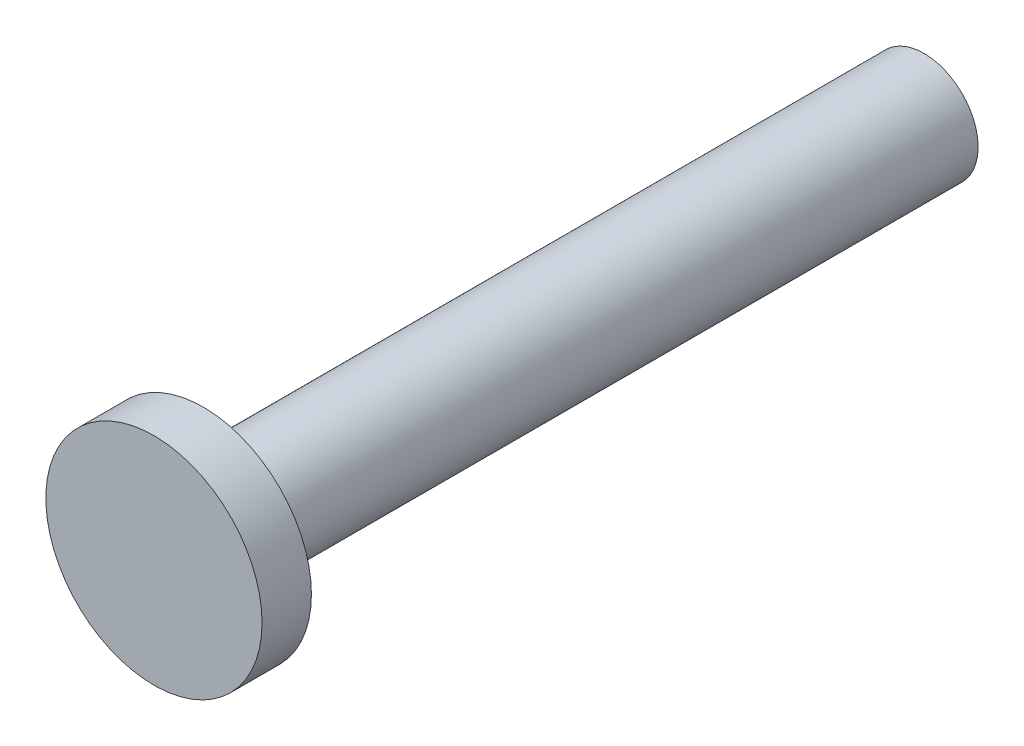
SolidWorks part; units mm, degrees
ref_plane "Plan de face" through (0, 0, 0) normal (0, 0, 1) x (1, 0, 0)
ref_plane "Plan de dessus" through (0, 0, 0) normal (0, 1, 0) x (1, 0, 0)
ref_plane "Plan de droite" through (0, 0, 0) normal (1, 0, 0) x (0, 0, -1)
sketch "Esquisse1" plane through (0, 0, 0) normal (0, 0, 1) x (1, 0, 0)
  circle A0 centre (0, 0) radius 3
  dimension "D1" = 6
extrude "Boss.-Extru.1" add sketch "Esquisse1" along normal blind 1.37
sketch "Esquisse2" plane through (0, 0, 0) normal (0, 0, -1) x (-1, 0, 0)
  circle A0 centre (0, 0) radius 1.5
  dimension "D1" = 3
extrude "Boss.-Extru.2" add sketch "Esquisse2" along normal blind 20
